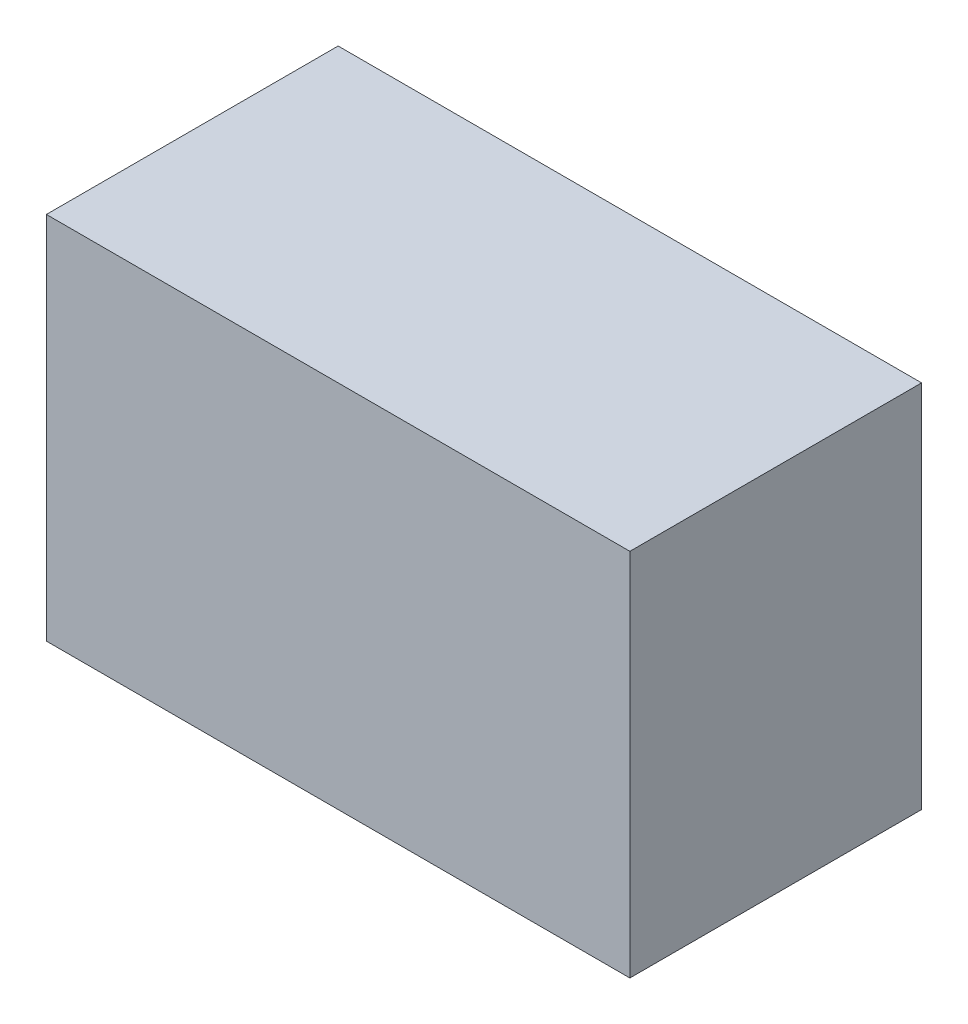
SolidWorks part; units mm, degrees
ref_plane "Plan1" through (0, 0, 0) normal (0, 0, 1) x (1, 0, 0)
ref_plane "Plan2" through (0, 0, 0) normal (0, 1, 0) x (1, 0, 0)
ref_plane "Plan3" through (0, 0, 0) normal (1, 0, 0) x (0, 0, -1)
sketch "Esquisse1" plane through (0, 0, 0) normal (0, 0, 1) x (1, 0, 0)
  line L1 (0, 0) -> (30, 0)
  line L2 (0, 0) -> (0, 19)
  line L3 (0, 19) -> (30, 19)
  line L4 (30, 0) -> (30, 19)
extrude "Base-Extrusion" add sketch "Esquisse1" along normal blind 15
